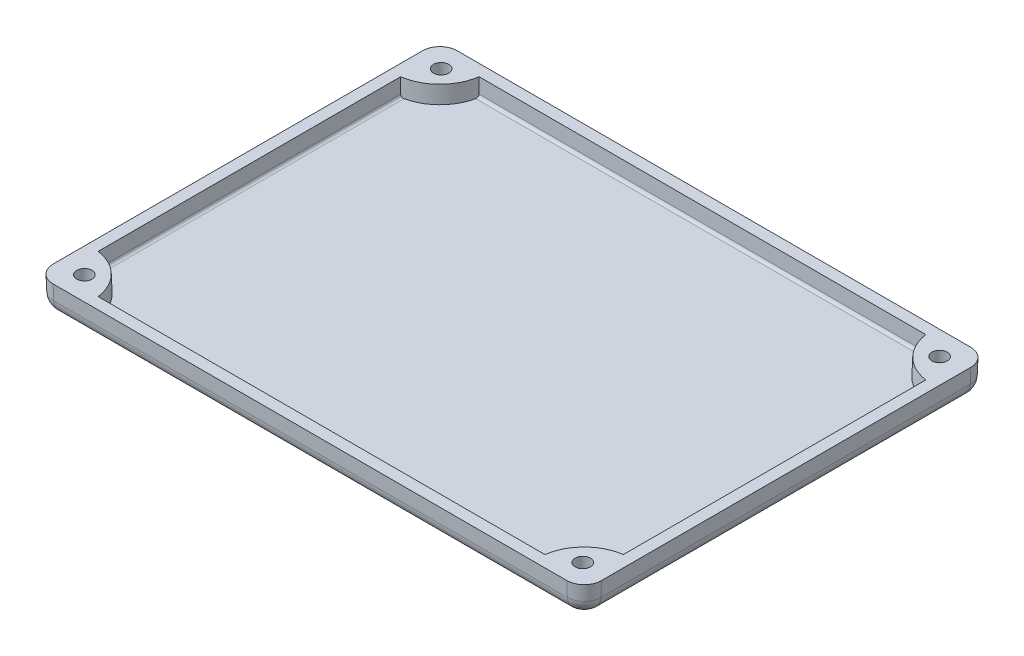
SolidWorks part; units mm, degrees
ref_plane "Front Plane" through (0, 0, 0) normal (0, 0, 1) x (1, 0, 0)
ref_plane "Top Plane" through (0, 0, 0) normal (0, 1, 0) x (1, 0, 0)
ref_plane "Right Plane" through (0, 0, 0) normal (1, 0, 0) x (0, 0, -1)
ref_plane "Plane1" through (0, 0, 0) normal (0, -1, 0) x (-1, 0, 0)
sketch "Sketch1" plane through (0, 0, 0) normal (0, -1, 0) x (-1, 0, 0)
  line L0 (44.5018, -35) -> (-44.5018, -35) construction
  line L1 (-47.5, 32.0018) -> (-47.5, -32.0018) construction
  line L2 (44.5018, 35) -> (-44.5018, 35) construction
  line L3 (47.5, 32.0018) -> (47.5, -32.0018) construction
  line L4 (44.5018, -35) -> (-44.5018, -35)
  line L5 (-47.5, 32.0018) -> (-47.5, -32.0018)
  line L6 (44.5018, 35) -> (-44.5018, 35)
  line L7 (47.5, 32.0018) -> (47.5, -32.0018)
  ellipse E0 centre (44.4982, -31.9982) end of major axis (46.6221, -34.1221) minor radius 3 (44.5018, -35) -> (47.5, -32.0018) ccw construction
  ellipse E1 centre (-44.4982, -31.9982) end of major axis (-46.6221, -34.1221) minor radius 3 (-47.5, -32.0018) -> (-44.5018, -35) ccw construction
  ellipse E2 centre (-44.4982, 31.9982) end of major axis (-46.6221, 34.1221) minor radius 3 (-44.5018, 35) -> (-47.5, 32.0018) ccw construction
  ellipse E3 centre (44.4982, 31.9982) end of major axis (46.6221, 34.1221) minor radius 3 (47.5, 32.0018) -> (44.5018, 35) ccw construction
  ellipse E4 centre (44.4982, -31.9982) end of major axis (46.6221, -34.1221) minor radius 3 (44.5018, -35) -> (47.5, -32.0018) ccw
  ellipse E5 centre (-44.4982, -31.9982) end of major axis (-46.6221, -34.1221) minor radius 3 (-47.5, -32.0018) -> (-44.5018, -35) ccw
  ellipse E6 centre (-44.4982, 31.9982) end of major axis (-46.6221, 34.1221) minor radius 3 (-44.5018, 35) -> (-47.5, 32.0018) ccw
  ellipse E7 centre (44.4982, 31.9982) end of major axis (46.6221, 34.1221) minor radius 3 (47.5, 32.0018) -> (44.5018, 35) ccw
extrude "Boss-Extrude1-MainBox" add sketch "Sketch1" along normal blind 5 draft 2
fillet "Fillet1" radius 2.5 8 edges at (-47.3254, -5, 0) (0, -5, 34.8254) (47.3254, -5, 0) (0, -5, -34.8254) (-46.7072, -5, -33.7653) (-46.2653, -5, 34.2072) (46.7072, -5, 33.7653) (46.2653, -5, -34.2072)
shell "Shell1" thickness 2
sketch "Sketch2" plane through (0, 0, 0) normal (0, 1, 0) x (1, 0, 0)
  line L0 (-47.5, 32.0018) -> (-44.5018, 35) construction
  line L1 (-46.6221, 26.1221) -> (-46.6221, 32.0018)
  line L2 (-46.6221, 32.0018) -> (-44.5018, 34.1221)
  line L3 (-44.5018, 34.1221) -> (-38.6221, 34.1221)
  line L6 (0, -2.75) -> (0, 2.75) construction
  line L7 (47.5, 32.0018) -> (44.5018, 35) construction
  line L8 (44.5018, 34.1221) -> (38.6221, 34.1221)
  line L9 (46.6221, 32.0018) -> (44.5018, 34.1221)
  line L10 (46.6221, 26.1221) -> (46.6221, 32.0018)
  line L11 (-2.75, 0) -> (2.75, 0) construction
  line L12 (47.5, -32.0018) -> (44.5018, -35) construction
  line L13 (46.6221, -26.1221) -> (46.6221, -32.0018)
  line L14 (46.6221, -32.0018) -> (44.5018, -34.1221)
  line L15 (44.5018, -34.1221) -> (38.6221, -34.1221)
  line L16 (-47.5, -32.0018) -> (-44.5018, -35) construction
  line L17 (-44.5018, -34.1221) -> (-38.6221, -34.1221)
  line L18 (-46.6221, -32.0018) -> (-44.5018, -34.1221)
  line L19 (-46.6221, -26.1221) -> (-46.6221, -32.0018)
  arc A0 (-46.6221, 26.1221) -> (-38.6221, 34.1221) centre (-46.6221, 34.1221) ccw
  arc A1 (46.6221, 26.1221) -> (38.6221, 34.1221) centre (46.6221, 34.1221) cw
  arc A2 (46.6221, -26.1221) -> (38.6221, -34.1221) centre (46.6221, -34.1221) ccw
  arc A3 (-46.6221, -26.1221) -> (-38.6221, -34.1221) centre (-46.6221, -34.1221) cw
  spline S0 degree 3 poles (-47.5, 32.0018) (-47.5, 32.3945) (-47.422, 32.7868) (-47.1217, 33.5121) (-46.8995, 33.8446) (-46.3446, 34.3995) (-46.0121, 34.6217) (-45.2868, 34.922) (-44.8945, 35) (-44.5018, 35) knots 5.498396 5.498396 5.498396 5.498396 5.890791 5.890791 6.283185 6.283185 6.67558 6.67558 7.067974 7.067974 7.067974 7.067974 construction
  point P5 (-46.0009, 33.5009)
  dimension "D1" = 8
extrude "Boss-Extrude2-Corners" add sketch "Sketch2" against normal up to next draft 2 draft outward yes
sketch "Sketch3" plane through (0, -5, 0) normal (0, -1, 0) x (1, 0, 0)
  line L0 (-44.5018, 34.9097) -> (44.5018, 34.9097) construction
  line L1 (0, -2.75) -> (0, 2.75) construction
  line L2 (2.75, 0) -> (-2.75, 0) construction
  circle A0 centre (-43.1807, 30.9097) radius 1.5
  circle A1 centre (43.1807, 30.9097) radius 1.5
  circle A2 centre (43.1807, -30.9097) radius 1.5
  circle A3 centre (-43.1807, -30.9097) radius 1.5
  dimension "D1" = 3
  dimension "D2" = 2
  dimension "D3" = 4
extrude "Cut-Extrude1-ScrewHoles" cut sketch "Sketch3" against normal blind 10 draft 2
